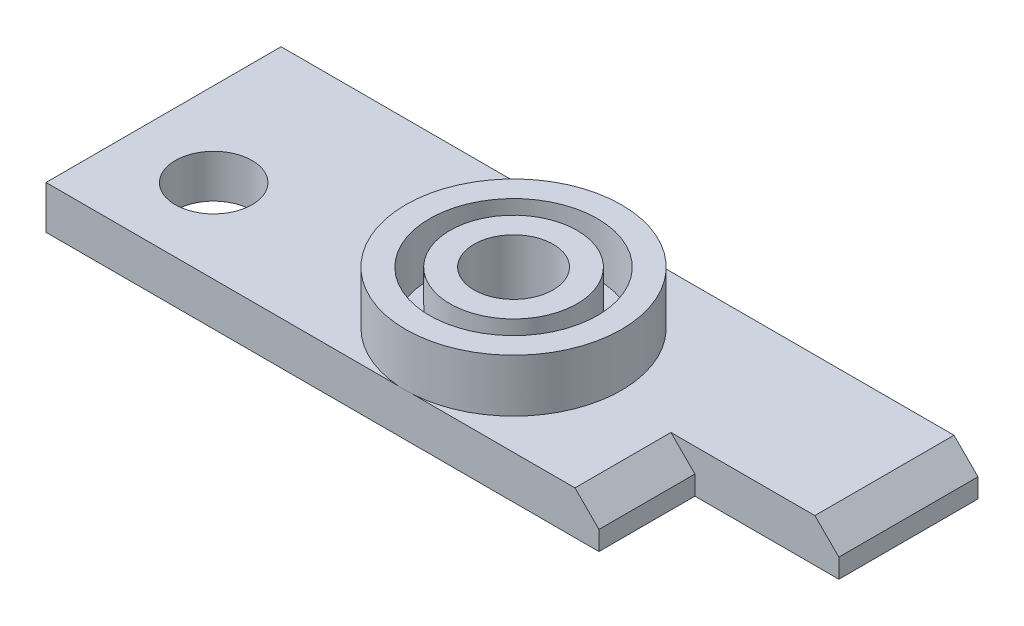
SolidWorks part; units mm, degrees
ref_plane "Front Plane" through (0, 0, 0) normal (0, 0, 1) x (1, 0, 0)
ref_plane "Top Plane" through (0, 0, 0) normal (0, 1, 0) x (1, 0, 0)
ref_plane "Right Plane" through (0, 0, 0) normal (1, 0, 0) x (0, 0, -1)
sketch "Sketch1" plane through (0, 0, 0) normal (0, 1, 0) x (1, 0, 0)
  line L1 (0, 0.2) -> (23.05, 0.2)
  line L2 (0, 4.2) -> (0, 10)
  line L3 (0, 10) -> (29.05, 10)
  line L4 (29.05, 4.2) -> (29.05, 10)
  line L5 (0, 4.2) -> (0, 0.2)
  line L6 (29.05, 4.2) -> (23.05, 4.2)
  line L7 (23.05, 4.2) -> (23.05, 0.2)
  dimension "D1" = 5.8
  dimension "D2" = 29.05
  dimension "D3" = 6
  dimension "D5" = 4
extrude "Boss-Extrude1" add sketch "Sketch1" along normal blind 1.8
sketch "Sketch3" plane through (0, 0, 0) normal (0, -1, 0) x (1, 0, 0)
  circle A0 centre (3.5, -3.6898) radius 1.6
  circle A1 centre (3.5, -3.6898) radius 2 construction
  dimension "D1" = 3.2
extrude "Cut-Extrude1" cut sketch "Sketch3" against normal through all
sketch "Sketch4" plane through (0, 0, 0) normal (0, -1, 0) x (1, 0, 0)
  circle A0 centre (15, -4.6898) radius 2.65
  circle A1 centre (15, -4.6898) radius 2.65 construction
extrude "Boss-Extrude2" add sketch "Sketch4" against normal blind 4
sketch "Sketch5" plane through (0, 4, 0) normal (0, 1, 0) x (1, 0, 0)
  circle A0 centre (15, 4.6898) radius 1.65
  circle A1 centre (15, 4.6898) radius 2.65 construction
  dimension "D1" = 1
extrude "Cut-Extrude2" cut sketch "Sketch5" against normal through all
sketch "Sketch7" plane through (0, 1.8, 0) normal (0, 1, 0) x (1, 0, 0)
  circle A0 centre (15, 4.6898) radius 4.5
  circle A1 centre (15, 4.6898) radius 3.5
  circle A4 centre (15, 4.6898) radius 4.5 construction
  circle A5 centre (15, 4.6898) radius 3.5 construction
extrude "Boss-Extrude4" add sketch "Sketch7" along normal up to surface (2.2 mm away) up to face at (15, 4, -3.0398)
chamfer "Chamfer2" distance 1 angle 45 2 edges at (23.05, 1.8, -2.2) (29.05, 1.8, -7.1)
